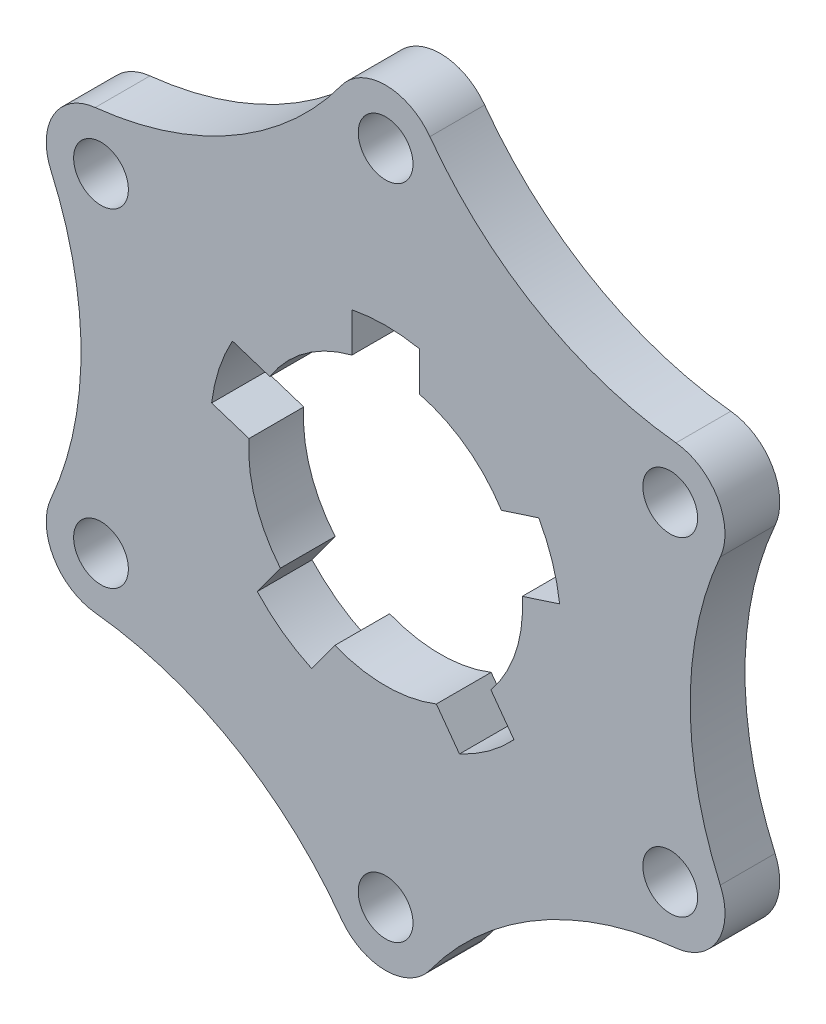
SolidWorks part; units mm, degrees
ref_plane "Alzado" through (0, 0, 0) normal (0, 0, 1) x (1, 0, 0)
ref_plane "Planta" through (0, 0, 0) normal (0, 1, 0) x (1, 0, 0)
ref_plane "Vista lateral" through (0, 0, 0) normal (1, 0, 0) x (0, 0, -1)
sketch "Croquis1" plane through (0, 0, 0) normal (0, 0, 1) x (1, 0, 0)
  line L0 (27.966, 15.5532) -> (21.1453, 13.337)
  line L2 (-6.15, 31.4035) -> (-6.15, 24.2317)
  line L4 (6.15, 31.4035) -> (6.15, 24.2317)
  line L5 (31.7669, 3.8552) -> (24.9462, 1.639)
  line L6 (23.4339, -21.7911) -> (19.2185, -15.989)
  line L7 (13.483, -29.0208) -> (9.2676, -23.2188)
  line L8 (-13.483, -29.0208) -> (-9.2676, -23.2188)
  line L9 (-23.4339, -21.7911) -> (-19.2185, -15.989)
  line L10 (-31.7669, 3.8552) -> (-24.9462, 1.639)
  line L11 (-27.966, 15.5532) -> (-21.1453, 13.337)
  circle A0 centre (0, 0) radius 60 construction
  circle A1 centre (0, 60) radius 5
  arc A2 (8.0816, 65.8896) -> (-8.0816, 65.8896) centre (0, 60) ccw
  arc A3 (61.1029, 25.9459) -> (53.0213, 39.9437) centre (51.9615, 30) ccw
  circle A4 centre (51.9615, 30) radius 5
  arc A5 (53.0213, -39.9437) -> (61.1029, -25.9459) centre (51.9615, -30) ccw
  circle A6 centre (51.9615, -30) radius 5
  arc A7 (-8.0816, -65.8896) -> (8.0816, -65.8896) centre (0, -60) ccw
  circle A8 centre (0, -60) radius 5
  arc A9 (-61.1029, -25.9459) -> (-53.0213, -39.9437) centre (-51.9615, -30) ccw
  circle A10 centre (-51.9615, -30) radius 5
  arc A11 (-53.0213, 39.9437) -> (-61.1029, 25.9459) centre (-51.9615, 30) ccw
  circle A12 centre (-51.9615, 30) radius 5
  arc A13 (-53.0213, 39.9437) -> (-8.0816, 65.8896) centre (-59.8038, 103.5833) ccw
  arc A14 (8.0816, 65.8896) -> (53.0213, 39.9437) centre (59.8038, 103.5833) ccw
  arc A15 (61.1029, 25.9459) -> (61.1029, -25.9459) centre (119.6077, 0) ccw
  arc A16 (53.0213, -39.9437) -> (8.0816, -65.8896) centre (59.8038, -103.5833) ccw
  arc A17 (-8.0816, -65.8896) -> (-53.0213, -39.9437) centre (-59.8038, -103.5833) ccw
  arc A18 (-61.1029, -25.9459) -> (-61.1029, 25.9459) centre (-119.6077, 0) ccw
  arc A21 (6.15, 31.4035) -> (-6.15, 31.4035) centre (0, 0) ccw
  arc A22 (-6.15, 24.2317) -> (-21.1453, 13.337) centre (0, 0) ccw
  arc A23 (31.7669, 3.8552) -> (27.966, 15.5532) centre (0, 0) ccw
  arc A24 (13.483, -29.0208) -> (23.4339, -21.7911) centre (0, 0) ccw
  arc A25 (-23.4339, -21.7911) -> (-13.483, -29.0208) centre (0, 0) ccw
  arc A26 (-27.966, 15.5532) -> (-31.7669, 3.8552) centre (0, 0) ccw
  arc A27 (-24.9462, 1.639) -> (-19.2185, -15.989) centre (0, 0) ccw
  arc A28 (21.1453, 13.337) -> (6.15, 24.2317) centre (0, 0) ccw
  arc A29 (19.2185, -15.989) -> (24.9462, 1.639) centre (0, 0) ccw
  arc A30 (-9.2676, -23.2188) -> (9.2676, -23.2188) centre (0, 0) ccw
  point P5 (0, 32)
  point P24 (0, 0)
  point P43 (0, 0)
  point P59 (0, 0)
  dimension "D1" = 120
  dimension "D2" = 10
  dimension "D3" = 20
  dimension "D5" = 64
  dimension "D7" = 50
  dimension "D8" = 64
  dimension "D9" = 12.3
  dimension "D4" = 6
  dimension "D6" = 6
  dimension "D10" = 5
extrude "Saliente-Extruir1" add sketch "Croquis1" along normal blind 10
